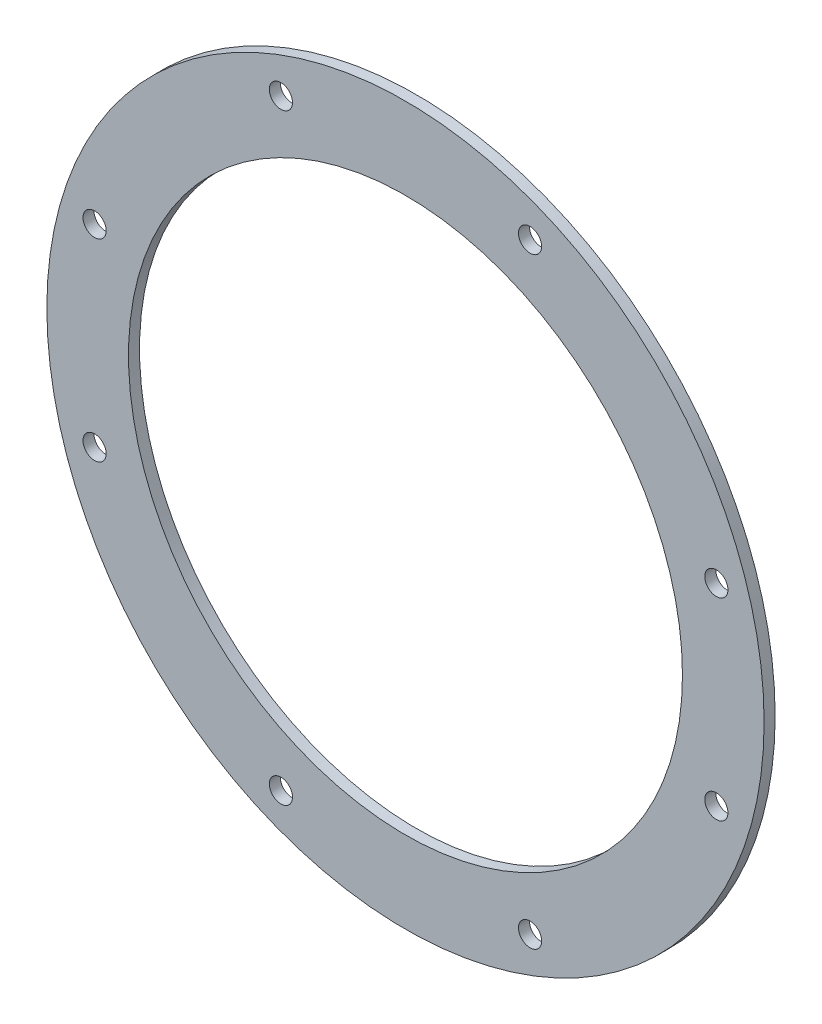
SolidWorks part; units mm, degrees
material "Thornel Mat VMA"
ref_plane "前视基准面" through (0, 0, 0) normal (0, 0, 1) x (1, 0, 0)
ref_plane "上视基准面" through (0, 0, 0) normal (0, 1, 0) x (1, 0, 0)
ref_plane "右视基准面" through (0, 0, 0) normal (1, 0, 0) x (0, 0, -1)
other "Configuration Table"
sketch "草图1" plane through (0, 0, 0) normal (0, 0, 1) x (1, 0, 0)
  line L0 (0, 59) -> (0, 0) construction
  line L1 (0, 0) -> (22.5783, 54.5089) construction
  line L3 (-56.3449, -17.5) -> (56.3449, -17.5) construction
  line L4 (-56.3449, -17.5) -> (-56.3449, 17.5) construction
  line L5 (-56.3449, 17.5) -> (56.3449, 17.5) construction
  line L6 (56.3449, -17.5) -> (56.3449, 17.5) construction
  line L7 (-56.3449, -17.5) -> (56.3449, 17.5) construction
  line L8 (-56.3449, 17.5) -> (56.3449, -17.5) construction
  circle A0 centre (0, 0) radius 50.2
  circle A1 centre (0, 0) radius 59 construction
  circle A2 centre (0, 0) radius 65
  circle A3 centre (22.5783, 54.5089) radius 2.1
  circle A6 centre (22.5783, -54.5089) radius 2.1
  circle A7 centre (-22.5783, -54.5089) radius 2.1
  circle A10 centre (-22.5783, 54.5089) radius 2.1
  circle A11 centre (-54.5089, 22.5783) radius 2.1 [skipped]
  circle A12 centre (-54.5089, -22.5783) radius 2.1 [skipped]
  circle A13 centre (54.5089, 22.5783) radius 2.1 [skipped]
  circle A14 centre (54.5089, -22.5783) radius 2.1 [skipped]
  circle A15 centre (56.3449, 17.5) radius 2.1
  circle A16 centre (56.3449, -17.5) radius 2.1
  circle A17 centre (-56.3449, 17.5) radius 2.1
  circle A18 centre (-56.3449, -17.5) radius 2.1
  point P32 (0, 0)
  dimension "D1" = 100.4
  dimension "D2" = 130
  dimension "D3" = 118
  dimension "D4" = 4.2
  dimension "D6" = 22.5
  dimension "D7" = 35
  dimension "D5" = 8
extrude "凸台-拉伸1" add sketch "草图1" along normal blind 2
